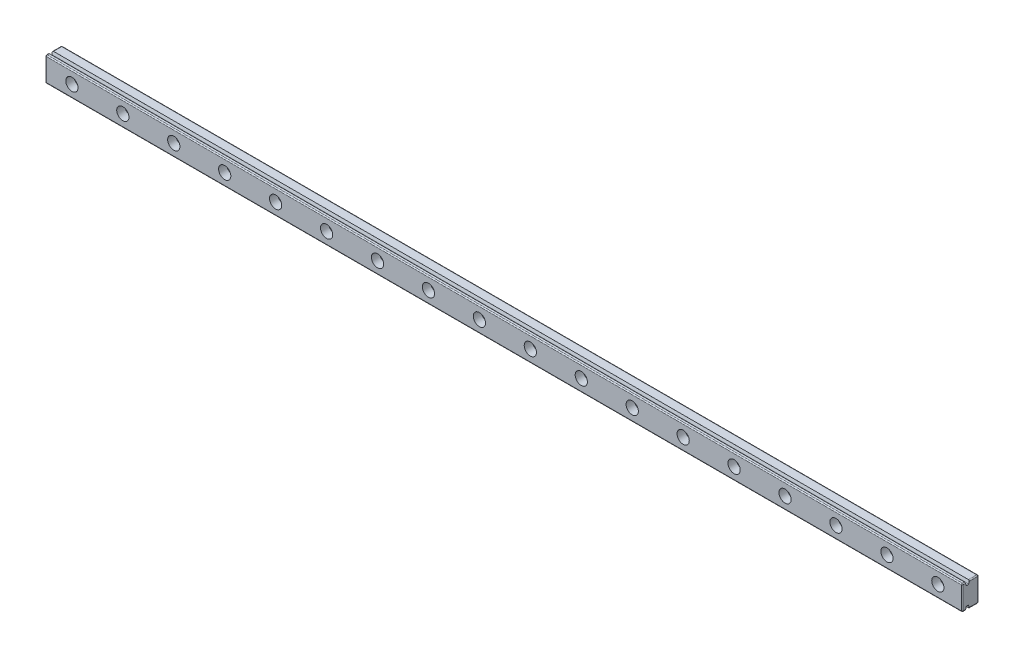
SolidWorks part; units mm, degrees
other "Markup1"
sketch "Sketch4" plane through (450, 6, 4) normal (0.5774, 0.5773, 0.5774) x (0.7071, 0, -0.7071)
ref_plane "Front Plane" through (0, 0, 0) normal (0, 0, 1) x (1, 0, 0)
ref_plane "Top Plane" through (0, 0, 0) normal (0, 1, 0) x (1, 0, 0)
ref_plane "Right Plane" through (0, 0, 0) normal (1, 0, 0) x (0, 0, -1)
sketch "Sketch1" plane through (0, 0, 0) normal (1, 0, 0) x (0, 0, -1)
  line L0 (-0.5, 6) -> (4, 6)
  line L1 (-4, 6) -> (-2.5, 6)
  line L2 (-4, 6) -> (-4, -6)
  line L3 (-4, -6) -> (-2.5, -6)
  line L4 (4, 6) -> (4, -6)
  line L5 (-4, 6) -> (4, -6) construction
  line L6 (-4, -6) -> (4, 6) construction
  line L8 (-2.5, 6) -> (-2.5, 4.25)
  line L9 (-2.5, 4.25) -> (-0.5, 4.25)
  line L10 (-0.5, 6) -> (-0.5, 4.25)
  line L12 (-2.5, -6) -> (-2.5, -4.25)
  line L13 (-2.5, -4.25) -> (-0.5, -4.25)
  line L14 (-0.5, -6) -> (-0.5, -4.25)
  line L15 (-0.5, -6) -> (4, -6)
  point P0 (0, 0)
  dimension "D1" = 12
  dimension "D2" = 8
  dimension "D3" = 2
  dimension "D4" = 2
  dimension "D5" = 1.5
  dimension "D6" = 1.5
  dimension "D7" = 8.5
  dimension "D8" = 4.25
extrude "Boss-Extrude1" add sketch "Sketch1" along normal blind 450
sketch "Sketch2" plane through (0, 0, 4) normal (0, 0, 1) x (1, 0, 0)
  line L0 (0, 6) -> (0, -6) construction
  circle A0 centre (13, 0) radius 1.75
  circle A1 centre (38, 0) radius 1.75
  circle A2 centre (63, 0) radius 1.75
  circle A3 centre (88, 0) radius 1.75
  circle A4 centre (113, 0) radius 1.75
  circle A5 centre (138, 0) radius 1.75
  circle A6 centre (163, 0) radius 1.75
  circle A7 centre (188, 0) radius 1.75
  circle A8 centre (213, 0) radius 1.75
  circle A9 centre (238, 0) radius 1.75
  circle A10 centre (263, 0) radius 1.75
  circle A11 centre (288, 0) radius 1.75
  circle A12 centre (313, 0) radius 1.75
  circle A13 centre (338, 0) radius 1.75
  circle A14 centre (363, 0) radius 1.75
  circle A15 centre (388, 0) radius 1.75
  circle A16 centre (413, 0) radius 1.75
  circle A17 centre (438, 0) radius 1.75
  dimension "D1" = 3.5
  dimension "D2" = 13
  dimension "D3" = 18
extrude "Cut-Extrude1" cut sketch "Sketch2" against normal blind 10
sketch "Sketch3" plane through (0, 0, 4) normal (0, 0, 1) x (1, 0, 0)
  circle A0 centre (13, 0) radius 3
  circle A1 centre (38, 0) radius 3
  circle A2 centre (63, 0) radius 3
  circle A3 centre (88, 0) radius 3
  circle A4 centre (113, 0) radius 3
  circle A5 centre (138, 0) radius 3
  circle A6 centre (163, 0) radius 3
  circle A7 centre (188, 0) radius 3
  circle A8 centre (213, 0) radius 3
  circle A9 centre (238, 0) radius 3
  circle A10 centre (263, 0) radius 3
  circle A11 centre (288, 0) radius 3
  circle A12 centre (313, 0) radius 3
  circle A13 centre (338, 0) radius 3
  circle A14 centre (363, 0) radius 3
  circle A15 centre (388, 0) radius 3
  circle A16 centre (413, 0) radius 3
  circle A17 centre (438, 0) radius 3
  dimension "D1" = 6
  dimension "D2" = 18
extrude "Cut-Extrude2" cut sketch "Sketch3" against normal blind 4
chamfer "Chamfer1" distance 0.5 angle 74 4 edges at (225, -4.25, 2.5) (225, -4.25, 0.5) (225, 4.25, 2.5) (225, 4.25, 0.5)
fillet "Fillet1" radius 0.5 20 edges at (450, -6, -1.75) (450, 0, -4) (450, 6, -1.75) (450, 6, 3.25) (450, 0, 4) (450, -6, 3.25) (0, -6, 3.25) (0, -6, -1.75) (0, 0, -4) (0, 6, -1.75) (0, 6, 3.25) (0, 0, 4) (225, -4.25, 1) (225, -4.25, 2) (225, 4.25, 2) (225, 4.25, 1) (225, -6, 4) (225, 6, 4) (225, -6, -4) (225, 6, -4)
